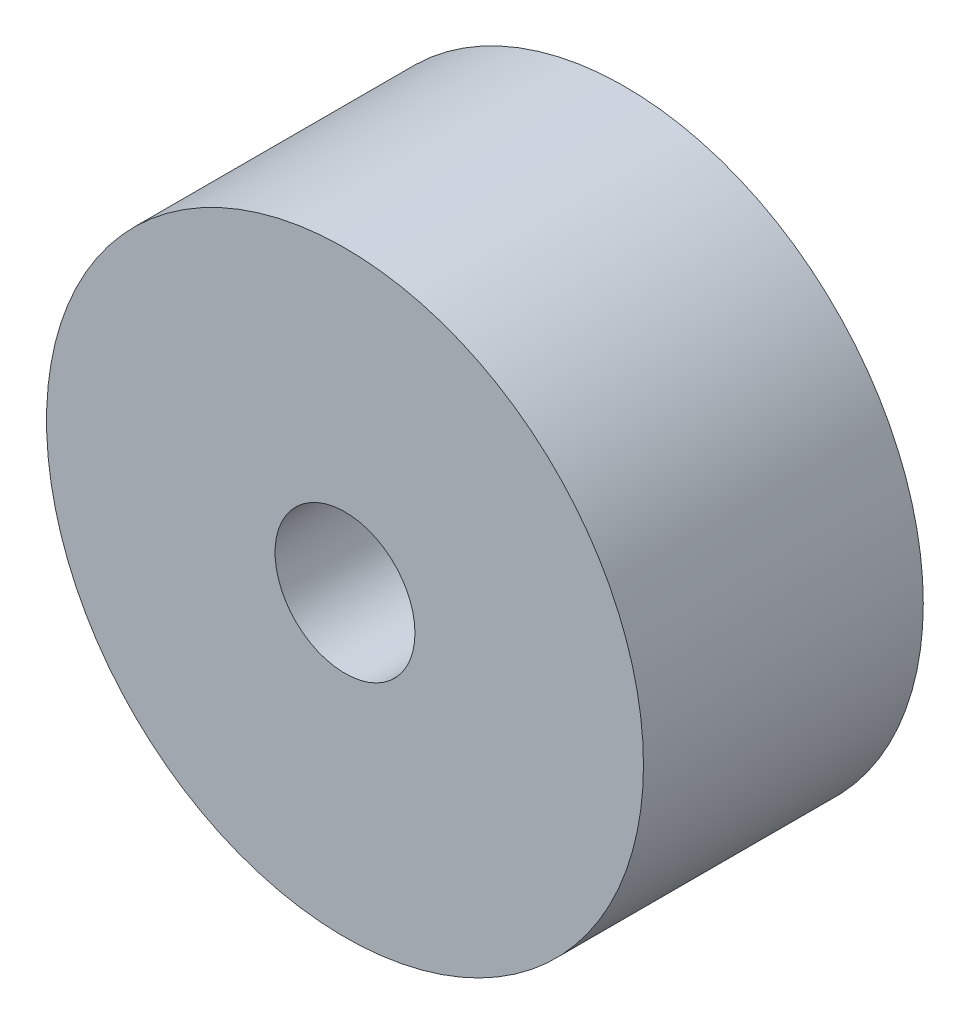
SolidWorks part; units mm, degrees
material "Rubber"
ref_plane "Front Plane" through (0, 0, 0) normal (0, 0, 1) x (1, 0, 0)
ref_plane "Top Plane" through (0, 0, 0) normal (0, 1, 0) x (1, 0, 0)
ref_plane "Right Plane" through (0, 0, 0) normal (1, 0, 0) x (0, 0, -1)
sketch "Sketch1" plane through (0, 0, 0) normal (0, 0, 1) x (1, 0, 0)
  circle A0 centre (0, 0) radius 320
  circle A1 centre (0, 0) radius 75
  dimension "D1" = 640
  dimension "D2" = 150
extrude "Boss-Extrude1" add sketch "Sketch1" along normal blind 300
